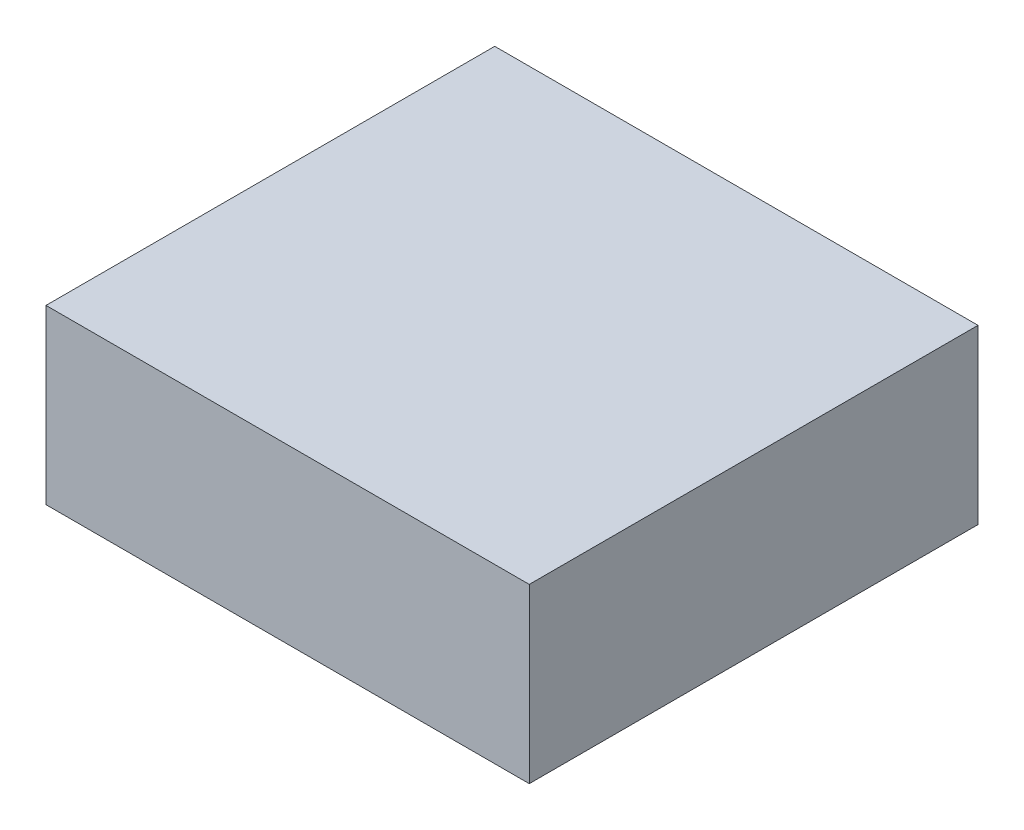
SolidWorks part; units mm, degrees
ref_plane "Front Plane" through (0, 0, 0) normal (0, 0, 1) x (1, 0, 0)
ref_plane "Top Plane" through (0, 0, 0) normal (0, 1, 0) x (1, 0, 0)
ref_plane "Right Plane" through (0, 0, 0) normal (1, 0, 0) x (0, 0, -1)
sketch "Sketch1" plane through (0, 0, 0) normal (0, 1, 0) x (1, 0, 0)
  line L1 (35, -32.5) -> (-35, -32.5)
  line L2 (35, -32.5) -> (35, 32.5)
  line L3 (35, 32.5) -> (-35, 32.5)
  line L4 (-35, -32.5) -> (-35, 32.5)
  line L5 (35, -32.5) -> (-35, 32.5) construction
  line L6 (35, 32.5) -> (-35, -32.5) construction
  point P0 (0, 0)
  dimension "D1" = 65
  dimension "D2" = 70
extrude "Boss-Extrude1" add sketch "Sketch1" along normal blind 25
